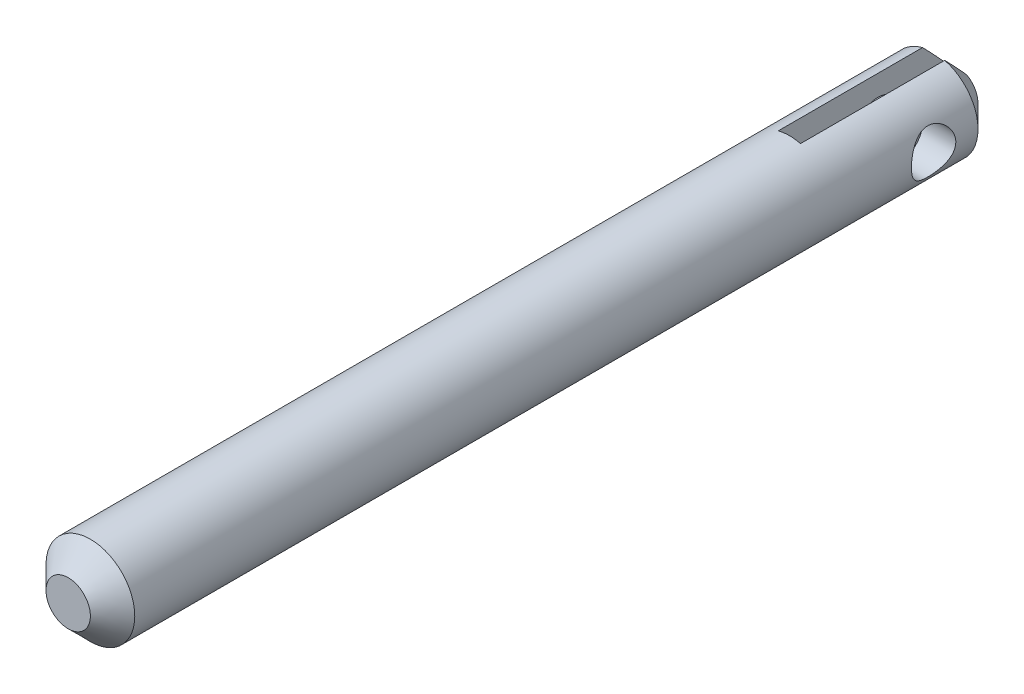
SolidWorks part; units mm, degrees
ref_plane "Спереди" through (0, 0, 0) normal (0, 0, 1) x (1, 0, 0)
ref_plane "Сверху" through (0, 0, 0) normal (0, 1, 0) x (1, 0, 0)
ref_plane "Справа" through (0, 0, 0) normal (1, 0, 0) x (0, 0, -1)
sketch "Эскиз1" plane through (0, 0, 0) normal (0, 0, 1) x (1, 0, 0)
  circle A0 centre (0, 0) radius 2
  dimension "D1" = 4
extrude "Штырь-толкатель" add sketch "Эскиз1" along normal blind 40
chamfer "Фаска1" distance 1 angle 45 2 edges at (2, 0, 0) (2, 0, 40)
sketch "Эскиз2" plane through (0, 0, 0) normal (0, 1, 0) x (1, 0, 0)
  line L0 (2, 0) -> (-2, 0) construction
  line L1 (-0.5, 0) -> (0.5, 0)
  line L2 (-0.5, 0) -> (-0.5, -7.5)
  line L3 (-0.5, -7.5) -> (0.5, -7.5)
  line L4 (0.5, 0) -> (0.5, -7.5)
  point P6 (0, -7.5)
  dimension "D1" = 7.5
  dimension "D2" = 1
extrude "Вырез под пластину" cut sketch "Эскиз2" against normal through all and the other way through all
sketch "Эскиз3" plane through (0, 0, 0) normal (1, 0, 0) x (0, 0, -1)
  circle A0 centre (-3, 0) radius 1
  point P2 (0, 0)
  dimension "D1" = 2
  dimension "D2" = 3
extrude "Вырез-Вытянуть2" cut sketch "Эскиз3" against normal through all and the other way through all
